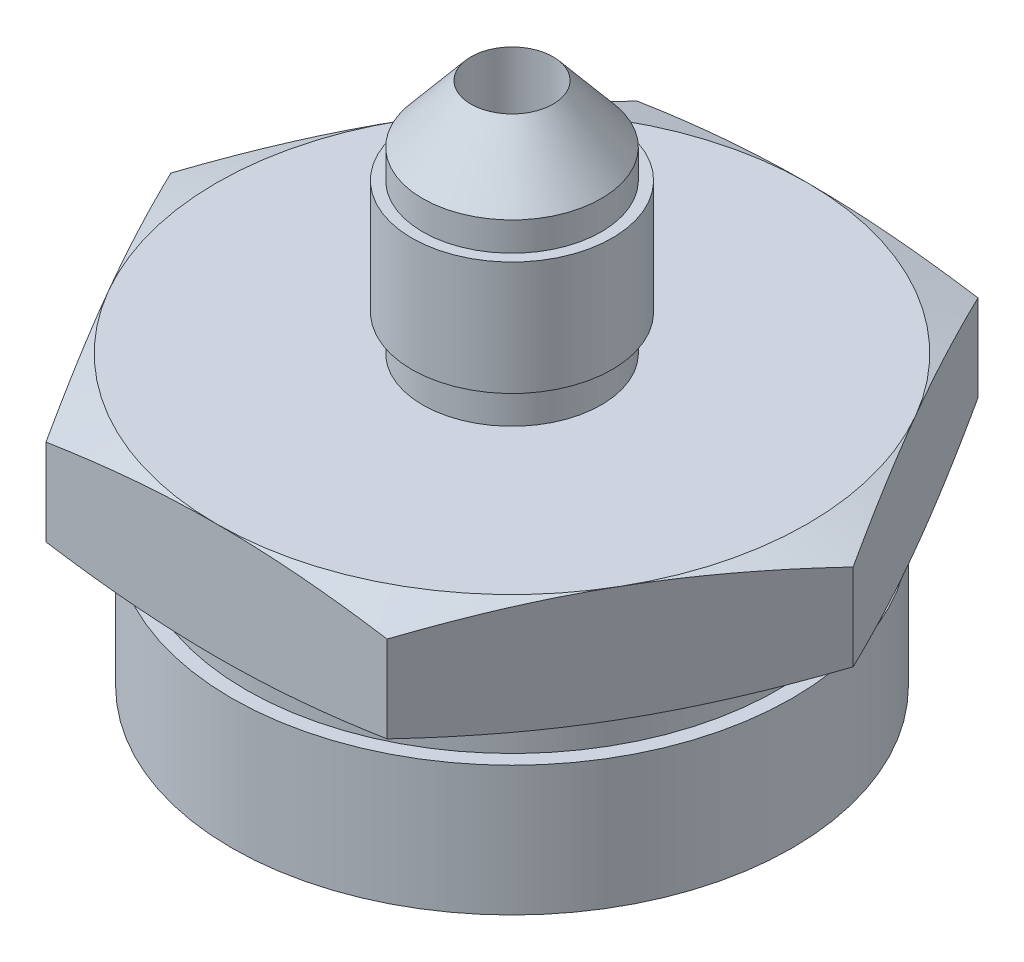
SolidWorks part; units mm, degrees
ref_plane "Спереди" through (0, 0, 0) normal (0, 0, 1) x (1, 0, 0)
ref_plane "Сверху" through (0, 0, 0) normal (0, 1, 0) x (1, 0, 0)
ref_plane "Справа" through (0, 0, 0) normal (1, 0, 0) x (0, 0, -1)
sketch "Эскиз2" plane through (0, 0, 0) normal (0, 1, 0) x (1, 0, 0)
  line L0 (-740.1494, 0) -> (36267.319, 0) construction
  line L1 (11.8357, -20.5) -> (23.6714, 0)
  line L2 (23.6714, 0) -> (11.8357, 20.5)
  line L3 (11.8357, 20.5) -> (-11.8357, 20.5)
  line L4 (-11.8357, 20.5) -> (-23.6714, 0)
  line L5 (-23.6714, 0) -> (-11.8357, -20.5)
  line L6 (-11.8357, -20.5) -> (11.8357, -20.5)
  circle A0 centre (0, 0) radius 20.5 construction
  point P1 (0, 0)
  dimension "D1" = 41
extrude "Бобышка-Вытянуть1" add sketch "Эскиз2" along normal blind 20
sketch "Эскиз3" plane through (0, 0, 0) normal (0, -1, 0) x (1, 0, 0)
  circle A0 centre (0, 0) radius 18.45
  dimension "D1" = 36.9
extrude "Вырез-Вытянуть1" cut sketch "Эскиз3" against normal blind 12 flip side to cut
sketch "Эскиз9" plane through (0, 20, 0) normal (0, 1, 0) x (1, 0, 0)
  line L1 (23.6714, 0) -> (20.5, 0)
  line L2 (11.8357, -20.5) -> (23.6714, 0) construction
  circle A0 centre (0, 0) radius 20.5
  dimension "D1" = 41
sketch "Эскиз10" plane through (0, 0, 0) normal (0, 0, 1) x (1, 0, 0)
  line L0 (23.6714, 20) -> (23.6714, 19)
  line L1 (23.6714, 20) -> (23.6714, 12) construction
  line L2 (23.6714, 19) -> (20.5, 20)
  line L3 (20.5, 20) -> (23.6714, 20)
  dimension "D1" = 1
ref_axis "Ось1" through (0, 12, 0) along (0, -1, 0)
revolve "Вырез-Повернуть1" cut sketch "Эскиз10" angle 360 about axis through (0, 12, 0) along (0, -1, 0)
ref_plane "Плоскость2" through (0, 16, 0) normal (0, -1, 0) x (-1, 0, 0)
mirror "Зеркальное отражение1" about plane through (0, 16, 0) normal (0, -1, 0) of "Вырез-Повернуть1"
sketch "Эскиз11" plane through (0, 0, 0) normal (0, -1, 0) x (1, 0, 0)
  circle A0 centre (0, 0) radius 16.7
  dimension "D1" = 33.4
extrude "Вырез-Вытянуть2" cut sketch "Эскиз11" against normal blind 1.5
sketch "Эскиз13" plane through (0, 0, 0) normal (0, -1, 0) x (1, 0, 0)
  circle A0 centre (0, 0) radius 15
  dimension "D1" = 30
extrude "Вырез-Вытянуть4" cut sketch "Эскиз13" against normal blind 17
ref_plane "Плоскость3" through (0, 3.5, 0) normal (0, -1, 0) x (-1, 0, 0)
sketch "Эскиз14" plane through (0, 3.5, 0) normal (0, -1, 0) x (-1, 0, 0)
  circle A2 centre (0, 0) radius 15.7
  circle A3 centre (0, 0) radius 15.7
  dimension "D1" = 1
extrude "Вырез-Вытянуть5" cut sketch "Эскиз14" against normal up to surface (13.5 mm away) up to face at (0, 17, -15)
sketch "Эскиз15" plane through (0, 0, 0) normal (0, 0, 1) x (1, 0, 0)
  line L0 (18.45, 0) -> (19.45, 0)
  line L1 (-18.45, 0) -> (18.45, 0) construction
  line L2 (19.45, 0) -> (19.45, 9)
  line L3 (19.45, 9) -> (18.45, 9)
  line L4 (18.45, 9) -> (18.45, 0)
  dimension "D1" = 1
  dimension "D2" = 9
ref_axis "Ось2" through (0, 17, 0) along (0, -1, 0)
revolve "Повернуть1" add sketch "Эскиз15" angle 360 about axis through (0, 17, 0) along (0, -1, 0)
sketch "Эскиз16" plane through (0, 20, 0) normal (0, 1, 0) x (1, 0, 0)
  circle A0 centre (0, 0) radius 6.2
  dimension "D1" = 12.4
extrude "Бобышка-Вытянуть2" add sketch "Эскиз16" along normal blind 2.5
sketch "Эскиз17" plane through (0, 22.5, 0) normal (0, 1, 0) x (1, 0, 0)
  circle A0 centre (0, 0) radius 6.95
  dimension "D1" = 13.9
extrude "Бобышка-Вытянуть3" add sketch "Эскиз17" along normal blind 7.9
sketch "Эскиз18" plane through (0, 30.4, 0) normal (0, 1, 0) x (1, 0, 0)
  circle A0 centre (0, 0) radius 6.2 construction
  circle A3 centre (0, 0) radius 6.2
extrude "Бобышка-Вытянуть4" add sketch "Эскиз18" along normal blind 2
sketch "Эскиз19" plane through (0, 0, 0) normal (0, 0, 1) x (1, 0, 0)
  line L0 (6.2, 32.4) -> (2.85, 36.4)
  line L1 (6.2, 32.4) -> (-6.2, 32.4) construction
  line L2 (2.85, 36.4) -> (0, 36.4)
  line L3 (0, 36.4) -> (0, 32.4)
  line L4 (0, 32.4) -> (6.2, 32.4)
  line L5 (0, -964.7827) -> (0, 49035.2173) construction
  dimension "D1" = 5.7
  dimension "D2" = 4
revolve "Повернуть2" add sketch "Эскиз19" angle 360 about L5
sketch "Эскиз21" plane through (0, 36.4, 0) normal (0, 1, 0) x (1, 0, 0)
  circle A0 centre (0, 0) radius 2.85 construction
  circle A1 centre (0, 0) radius 2.85
extrude "Вырез-Вытянуть6" cut sketch "Эскиз21" against normal through all
sketch "Эскиз22" plane through (0, 0, 0) normal (0, 0, 1) x (1, 0, 0)
  line L0 (0, 20.1233) -> (5.4097, 17)
  line L1 (-15.7, 17) -> (15.7, 17) construction
  line L2 (5.4097, 17) -> (0, 17)
  line L3 (0, 17) -> (0, 20.1233)
  dimension "D1" = 30
revolve "Вырез-Повернуть2" cut sketch "Эскиз22" angle 360 about L3
